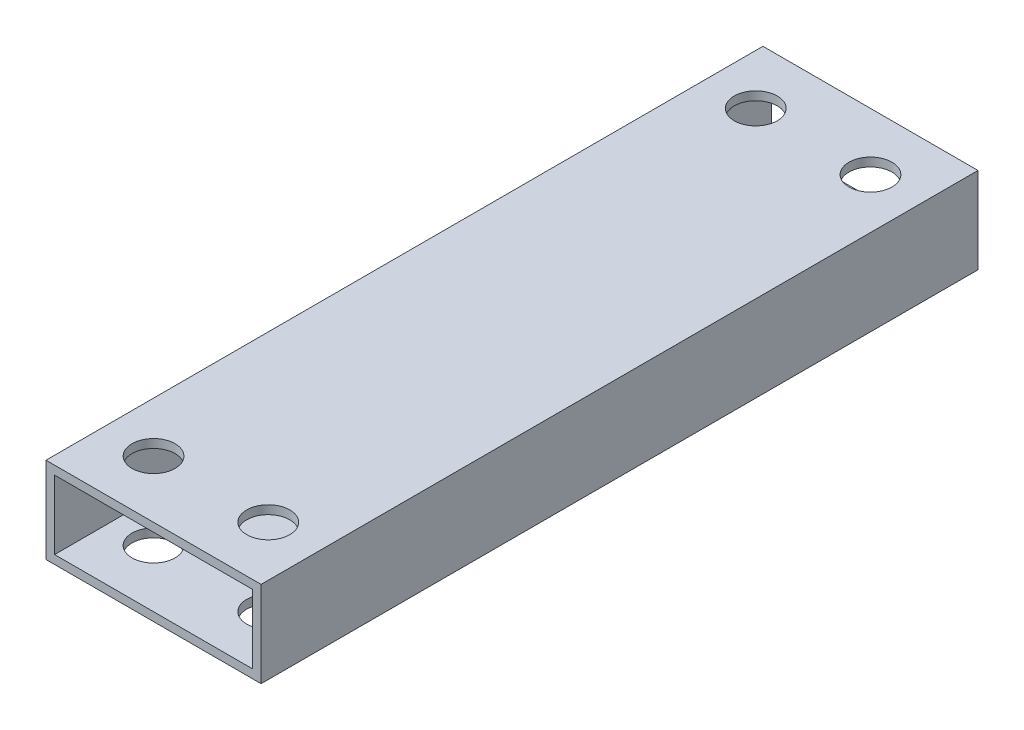
SolidWorks part; units mm, degrees
ref_plane "前视基准面" through (0, 0, 0) normal (0, 0, 1) x (1, 0, 0)
ref_plane "上视基准面" through (0, 0, 0) normal (0, 1, 0) x (1, 0, 0)
ref_plane "右视基准面" through (0, 0, 0) normal (1, 0, 0) x (0, 0, -1)
sketch "草图2" plane through (0, 0, 0) normal (0, 0, 1) x (1, 0, 0)
  line L1 (7.5, -3) -> (-7.5, -3)
  line L2 (7.5, -3) -> (7.5, 3)
  line L3 (7.5, 3) -> (-7.5, 3)
  line L4 (-7.5, -3) -> (-7.5, 3)
  line L5 (0, 3) -> (0, -3) construction
  line L6 (7.5, 0) -> (-7.5, 0) construction
  line L7 (6.9, -2.4) -> (-6.9, -2.4)
  line L8 (6.9, -2.4) -> (6.9, 2.4)
  line L9 (6.9, 2.4) -> (-6.9, 2.4)
  line L10 (-6.9, -2.4) -> (-6.9, 2.4)
  line L11 (0, 2.4) -> (0, -2.4) construction
  line L12 (6.9, 0) -> (-6.9, 0) construction
  point P0 (0, 0)
  point P4 (0, 0)
  dimension "D1" = 6
  dimension "D2" = 15
  dimension "D3" = 0.6
  dimension "D4" = 0.6
extrude "凸台-拉伸1" add sketch "草图2" along normal blind 50
sketch "草图3" plane through (0, 3, 0) normal (0, 1, 0) x (1, 0, 0)
  line L0 (7.5, -25) -> (-1.7403, -25) construction
  line L1 (7.5, -50) -> (7.5, 0) construction
  line L2 (7.5, 0) -> (-7.5, 0) construction
  line L3 (0, 0) -> (0, -6.4372) construction
  circle A0 centre (-4, -4) radius 1.5
  circle A1 centre (4, -4) radius 1.5
  circle A2 centre (4, -46) radius 1.5
  circle A3 centre (-4, -46) radius 1.5
  dimension "D2" = 3
  dimension "D1" = 8
  dimension "D3" = 4
extrude "切除-拉伸1" cut sketch "草图3" against normal blind 80
